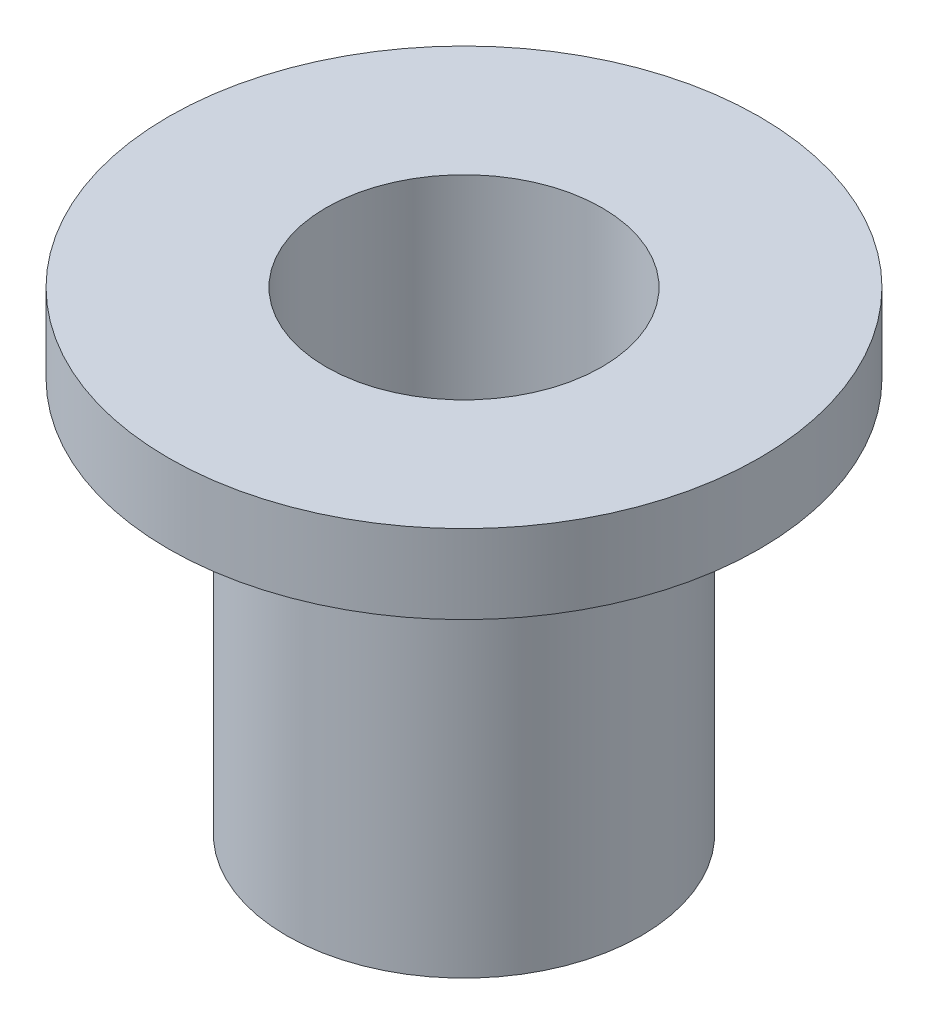
SolidWorks part; units mm, degrees
ref_plane "Front Plane" through (0, 0, 0) normal (0, 0, 1) x (1, 0, 0)
ref_plane "Top Plane" through (0, 0, 0) normal (0, 1, 0) x (1, 0, 0)
ref_plane "Right Plane" through (0, 0, 0) normal (1, 0, 0) x (0, 0, -1)
sketch "Sketch2" plane through (0, 0, 0) normal (0, 1, 0) x (1, 0, 0)
  circle A0 centre (0, 0) radius 3.5
  circle A1 centre (0, 0) radius 4.5
  dimension "D1" = 7
  dimension "D2" = 9
extrude "Boss-Extrude1" add sketch "Sketch2" along normal blind 10
sketch "Sketch3" plane through (0, 10, 0) normal (0, 1, 0) x (1, 0, 0)
  circle A0 centre (0, 0) radius 7.5
  circle A1 centre (0, 0) radius 3.5
  dimension "D1" = 15
  dimension "D2" = 7
extrude "Boss-Extrude2" add sketch "Sketch3" along normal blind 2
